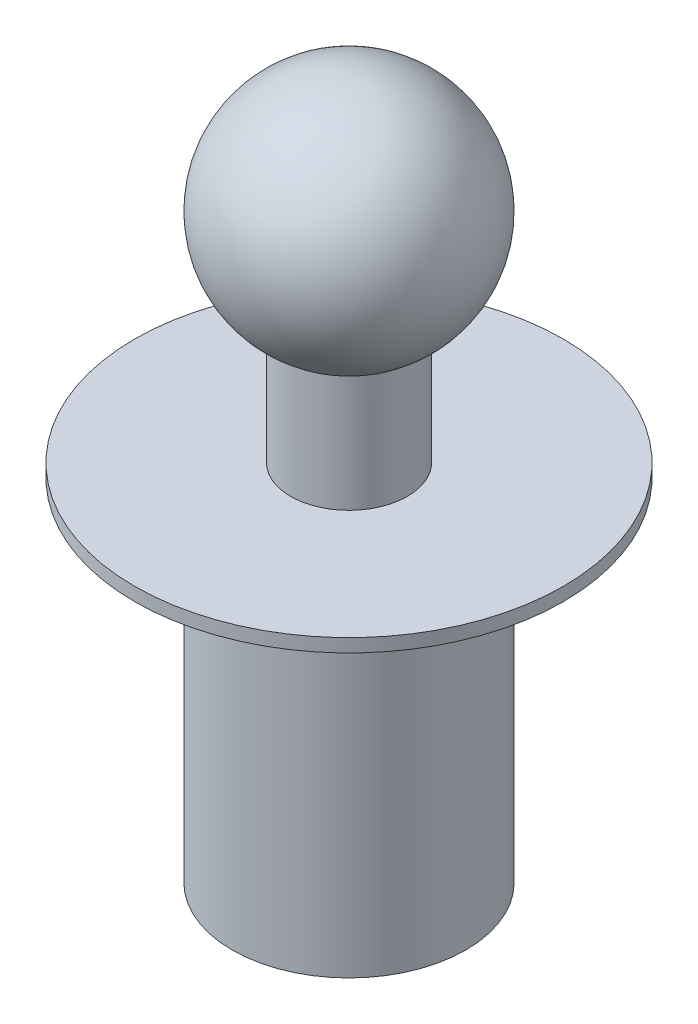
SolidWorks part; units mm, degrees
ref_plane "Plan de face" through (0, 0, 0) normal (0, 0, 1) x (1, 0, 0)
ref_plane "Plan de dessus" through (0, 0, 0) normal (0, 1, 0) x (1, 0, 0)
ref_plane "Plan de droite" through (0, 0, 0) normal (1, 0, 0) x (0, 0, -1)
sketch "Esquisse1" plane through (0, 0, 0) normal (0, 0, 1) x (1, 0, 0)
  line L0 (0, -3) -> (1, -3)
  line L1 (1, -3) -> (1, 0)
  line L2 (1, 0) -> (1.8346, 0)
  line L3 (1.8346, 0) -> (1.8346, 0.1138)
  line L4 (1.8346, 0.1138) -> (0.5, 0.1138)
  line L5 (0.5, 0.1138) -> (0.5, 1.1138)
  line L6 (0, -3) -> (0, 2.9798)
  line L7 (0.2938, 2.9798) -> (7.2728, 2.9798) construction
  arc A0 (0.5, 1.1138) -> (0, 2.9798) centre (0, 1.9798) ccw
  point P12 (0.5243, 1.454)
  point P13 (0, 4.181)
  point P14 (0, 0)
  point P15 (0, 2.7623)
  dimension "D2" = 1
  dimension "D1" = 1
  dimension "D3" = 0.5
  dimension "D4" = 3
  dimension "D5" = 1
revolve "Révolution1" add sketch "Esquisse1" angle 360 about L6
